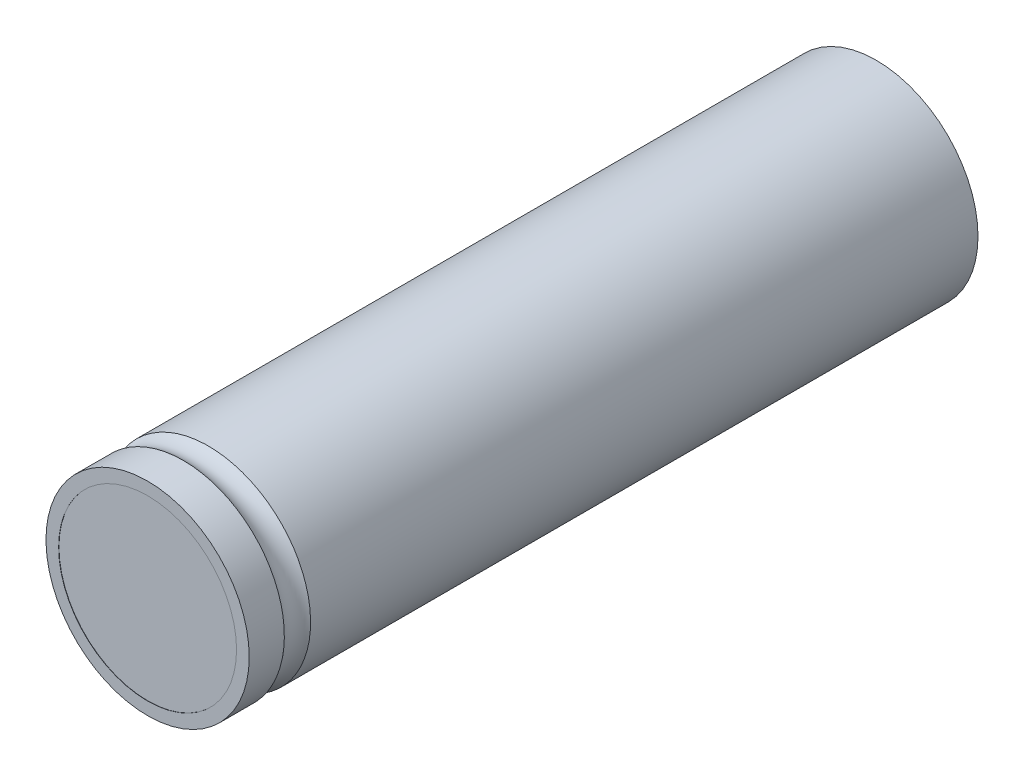
SolidWorks part; units mm, degrees
ref_plane "Front" through (0, 0, 0) normal (0, 0, 1) x (1, 0, 0)
ref_plane "Top" through (0, 0, 0) normal (0, 1, 0) x (1, 0, 0)
ref_plane "Right" through (0, 0, 0) normal (1, 0, 0) x (0, 0, -1)
sketch "Sketch1" plane through (0, 0, 0) normal (0, 0, 1) x (1, 0, 0)
  circle A1 centre (0, 0) radius 9.0678
extrude "Boss-Extrude1" add sketch "Sketch1" along normal blind 65.024
sketch "Sketch2" plane through (0, 0, 0) normal (1, 0, 0) x (0, 0, -1)
  line L0 (3.3279, 0.0462) -> (-75.4382, 0.0462) construction
  line L1 (-65.024, -27.0186) -> (-71.5544, -27.0186) construction
  line L2 (-65.024, 9.0678) -> (-72.9852, 9.0678) construction
  line L3 (-70.1235, 9.0678) -> (-70.1235, -27.0186) construction
  line L4 (-70.1235, -8.9754) -> (-76.3239, -8.9754) construction
  line L5 (3.3279, -17.997) -> (-75.4382, -17.997) construction
  line L6 (-61.9805, 9.1981) -> (-59.4608, 9.1981)
  arc A0 (-61.9805, 9.1981) -> (-59.4608, 9.1981) centre (-60.7206, 10.4436) ccw
revolve "Cut-Revolve9" cut sketch "Sketch2" angle 360 about L0
sketch "Sketch4" plane through (0, 0, 65.024) normal (0, 0, 1) x (1, 0, 0)
  circle A0 centre (0, 0) radius 7.9372
extrude "Cut-Extrude1" cut sketch "Sketch4" against normal blind 0.0254
sketch "Sketch5" plane through (0, 0, 0) normal (0, 0, -1) x (-1, 0, 0)
  circle A0 centre (0, 0) radius 7.7596
extrude "Cut-Extrude2" cut sketch "Sketch5" against normal blind 0.0254
sketch "Sketch6" plane through (0, 0, 0.0254) normal (0, 0, -1) x (-1, 0, 0)
  circle A0 centre (0, 0) radius 4.7375
extrude "Cut-Extrude3" cut sketch "Sketch6" against normal blind 0.0254
sketch "Sketch7" plane through (0, 0, 0.0508) normal (0, 0, -1) x (-1, 0, 0)
  line L0 (0.8854, 0.787) -> (2.5085, 0.787)
  line L1 (-2.115, 0.787) -> (-0.664, 0.787)
  line L2 (-2.115, 0.787) -> (-2.115, -0.541)
  line L3 (-2.115, -0.541) -> (-0.664, -0.541)
  line L4 (2.5085, 0.787) -> (2.5085, -0.541)
  line L5 (-0.664, 2.0904) -> (0.8854, 2.0904)
  line L6 (-0.664, 2.0904) -> (-0.664, 0.787)
  line L7 (-0.664, -1.9429) -> (0.8854, -1.9429)
  line L8 (0.8854, 2.0904) -> (0.8854, 0.787)
  line L9 (0.8854, -0.541) -> (2.5085, -0.541)
  line L10 (-0.664, -0.541) -> (-0.664, -1.9429)
  line L11 (0.8854, -0.541) -> (0.8854, -1.9429)
extrude "Cut-Extrude4" cut sketch "Sketch7" against normal blind 0.0254
